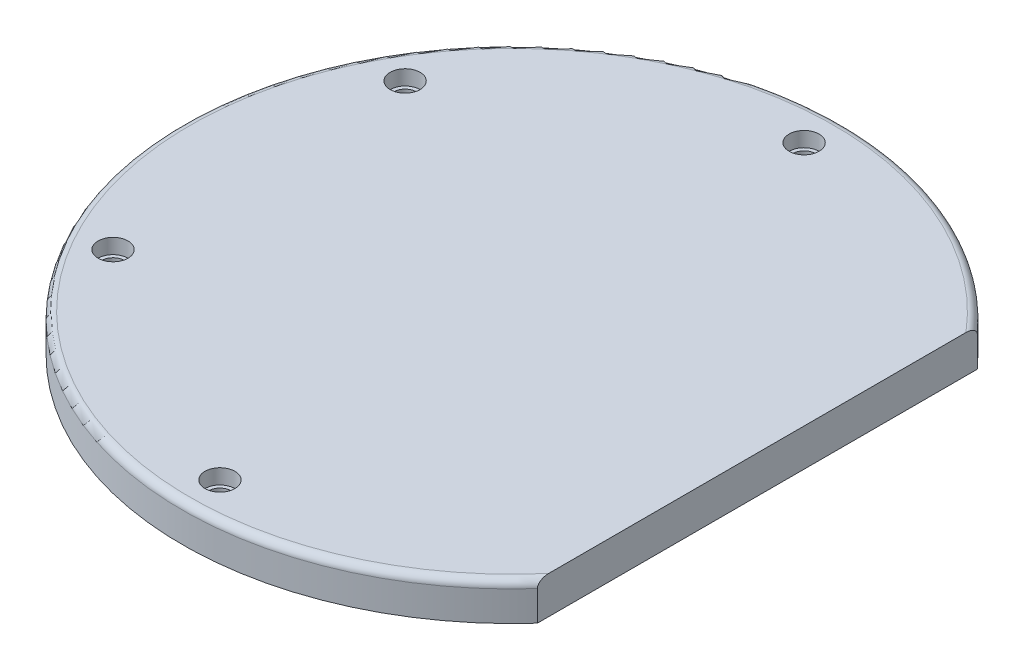
SolidWorks part; units mm, degrees
ref_plane "Спереди" through (0, 0, 0) normal (0, 0, 1) x (1, 0, 0)
ref_plane "Сверху" through (0, 0, 0) normal (0, 1, 0) x (1, 0, 0)
ref_plane "Справа" through (0, 0, 0) normal (1, 0, 0) x (0, 0, -1)
sketch "Эскиз1" plane through (0, 0, 0) normal (1, 0, 0) x (0, 0, -1)
  line L0 (0, 0) -> (0, 40.3421) construction
  line L1 (0, 0) -> (44, 0)
  line L2 (44, 0) -> (44, 4)
  line L3 (43, 5) -> (0, 5)
  line L4 (0, 5) -> (0, 0)
  arc A0 (43, 5) -> (44, 4) centre (43, 4) cw
  point P12 (44, 5)
  dimension "D5" = 1
  dimension "D1" = 44
  dimension "D3" = 5
revolve "Повернуть1" add sketch "Эскиз1" angle 360 about L0
sketch "Эскиз2" plane through (0, 0, 0) normal (1, 0, 0) x (0, 0, -1)
  line L0 (-39, 0) -> (-39, 15.7051) construction
  line L1 (-44, 0) -> (44, 0) construction
  line L2 (-39, 0) -> (-37.5, 0)
  line L3 (-37.5, 0) -> (-37.5, 3)
  line L5 (-37, 3) -> (-37, 5)
  line L6 (43, 5) -> (-43, 5) construction
  line L7 (-37, 5) -> (-39, 5)
  line L8 (-39, 5) -> (-39, 0)
  line L9 (-37.5, 3) -> (-37, 3)
  dimension "D1" = 39
  dimension "D2" = 1.5
  dimension "D3" = 2
  dimension "D4" = 2
revolve "Вырез-Повернуть1" cut sketch "Эскиз2" angle 360 about L0
pattern_circular "Круговой массив1" count 4 every 60 about axis through (0, 0, 0) along (0, 1, 0) of "Вырез-Повернуть1"
sketch "Эскиз3" plane through (0, 0, 0) normal (0, -1, 0) x (1, 0, 0)
  line L0 (32.7595, -29.3737) -> (32.7595, 29.3737) construction
  line L1 (32.7595, 29.3737) -> (32.7595, -29.3737)
  arc A0 (32.7595, -29.3737) -> (32.7595, 29.3737) centre (0, 0) ccw
extrude "Вырез-Вытянуть1" cut sketch "Эскиз3" against normal through all
